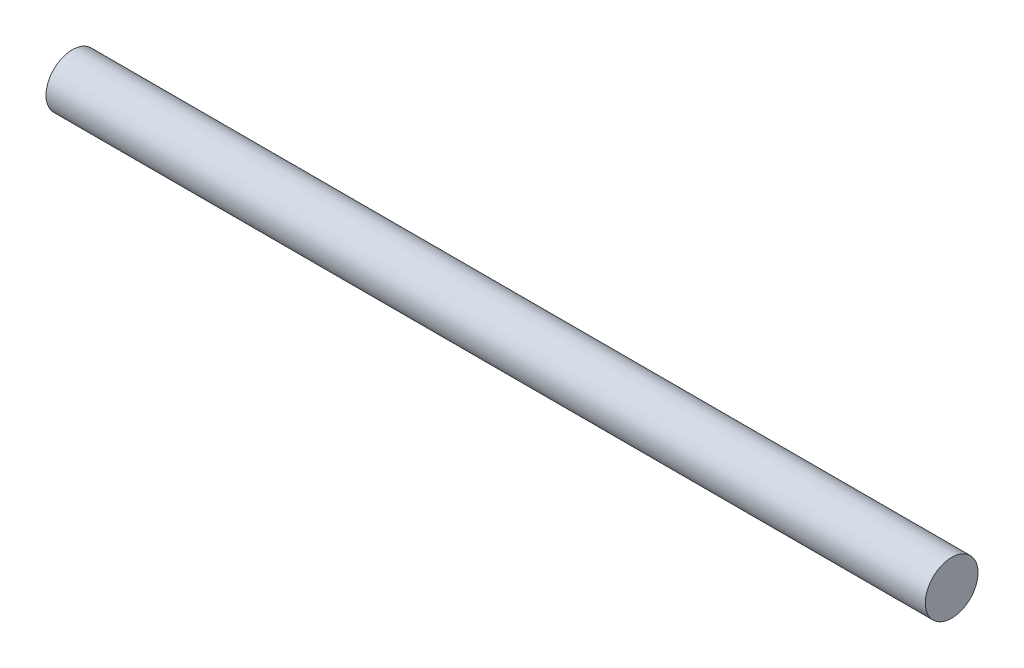
SolidWorks part; units mm, degrees
ref_plane "Front Plane" through (0, 0, 0) normal (0, 0, 1) x (1, 0, 0)
ref_plane "Top Plane" through (0, 0, 0) normal (0, 1, 0) x (1, 0, 0)
ref_plane "Right Plane" through (0, 0, 0) normal (1, 0, 0) x (0, 0, -1)
sketch "Sketch1" plane through (0, 0, 0) normal (0, 0, 1) x (1, 0, 0)
  line L1 (-46.0575, 2.286) -> (30.1425, 2.286)
  line L2 (-46.0575, 2.286) -> (-46.0575, 0)
  line L3 (-46.0575, 0) -> (30.1425, 0)
  line L4 (30.1425, 2.286) -> (30.1425, 0)
  dimension "D1" = 2.286
revolve "Revolve1" add sketch "Sketch1" angle 360 about L1
